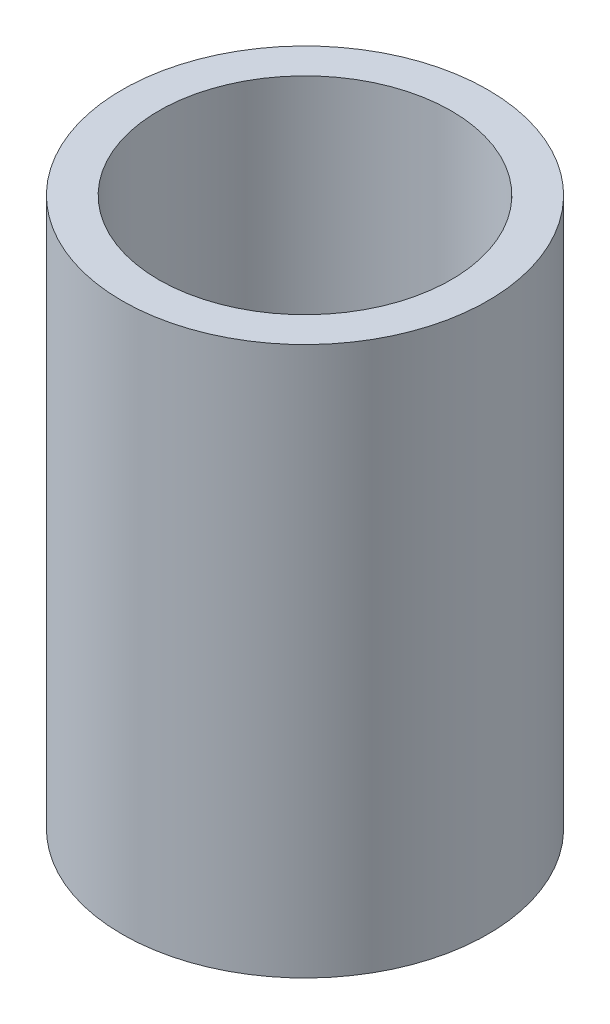
SolidWorks part; units mm, degrees
ref_plane "Front Plane" through (0, 0, 0) normal (0, 0, 1) x (1, 0, 0)
ref_plane "Top Plane" through (0, 0, 0) normal (0, 1, 0) x (1, 0, 0)
ref_plane "Right Plane" through (0, 0, 0) normal (1, 0, 0) x (0, 0, -1)
sketch "Sketch2" plane through (0, 0, 0) normal (0, 1, 0) x (1, 0, 0)
  circle A0 centre (0, 0) radius 50
  circle A1 centre (0, 0) radius 40
  dimension "D2" = 100
  dimension "D1" = 10
extrude "Boss-Extrude1" add sketch "Sketch2" along normal blind 150
sketch "Sketch3" plane through (0, 0, 0) normal (0, -1, 0) x (1, 0, 0)
  circle A1 centre (0, 0) radius 50
  circle A2 centre (0, 0) radius 50
  circle A3 centre (0, 0) radius 40 construction
  circle A4 centre (0, 0) radius 40
  circle A5 centre (0, 0) radius 30
  circle M4 centre (0, 0) radius 40
  dimension "10" = 10
  dimension "D1" = 0
extrude "Boss-Extrude2" add sketch "Sketch3" against normal blind 10 contours A5 M4
equation "\"Grosor de Pared\"= 10"
equation "\"D1@Sketch2\"=\"Grosor de Pared\""
equation "\"Diámetro Exterior\"= 100"
equation "\"D2@Sketch2\"=\"Diámetro Exterior\""
equation "\"Altura\"= 150"
equation "\"D1@Boss-Extrude1\"=\"Altura\""
equation "\"Diametro Escalón\"= 10"
equation "\"10@Sketch3\"=\"Diametro Escalón\""
equation "\"Altura Escalón\"= 10"
equation "\"D1@Boss-Extrude2\"=\"Altura Escalón\""
